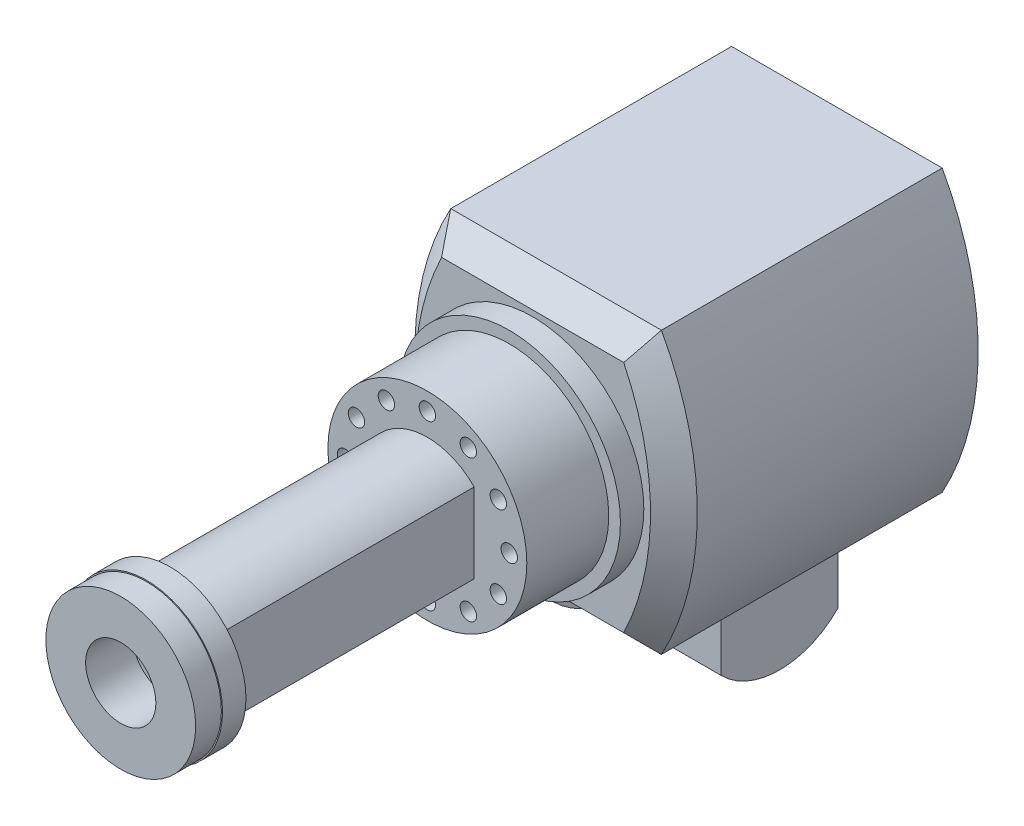
SolidWorks part; units mm, degrees
ref_plane "Front Plane" through (0, 0, 0) normal (0, 0, 1) x (1, 0, 0)
ref_plane "Top Plane" through (0, 0, 0) normal (0, 1, 0) x (1, 0, 0)
ref_plane "Right Plane" through (0, 0, 0) normal (1, 0, 0) x (0, 0, -1)
sketch "Sketch1" plane through (0, 0, 0) normal (0, 0, 1) x (1, 0, 0)
  line L0 (0, -116.0273) -> (0, 116.0273) construction
  line L1 (57.0057, 0) -> (-57.0057, 0) construction
  line L2 (45, 60) -> (-45, 60)
  line L3 (45, -60) -> (-45, -60)
  arc A0 (-45, 60) -> (-45, -60) centre (64.6586, 0) ccw
  arc A1 (45, 60) -> (45, -60) centre (-64.6586, 0) cw
  point P4 (0, 0)
  point P8 (0, 0)
  point P11 (0, 60)
  dimension "D3" = 125
  dimension "D1" = 60
  dimension "D2" = 90
extrude "Boss-Extrude1" add sketch "Sketch1" along normal blind 120 contours A1 L3 A0 L2
sketch "Sketch2" plane through (0, 0, 120) normal (0, 0, 1) x (1, 0, 0)
  line L2 (45, 60) -> (-45, 60)
  line L3 (-45, -60) -> (45, -60)
  line L4 (45, 60) -> (-45, 60)
  line L5 (-45, -60) -> (45, -60)
  arc A2 (-45, 60) -> (-45, -60) centre (64.6586, 0) ccw
  arc A3 (45, -60) -> (45, 60) centre (-64.6586, 0) ccw
  arc A4 (-45, 60) -> (-45, -60) centre (64.6586, 0) ccw
  arc A5 (45, -60) -> (45, 60) centre (-64.6586, 0) ccw
  dimension "D1" = 0
extrude "Boss-Extrude2" add sketch "Sketch2" along normal blind 10 draft 45
sketch "Sketch3" plane through (0, 0, 130) normal (0, 0, 1) x (1, 0, 0)
  circle A0 centre (0, 0) radius 47.5
  dimension "D1" = 95
extrude "Boss-Extrude3" add sketch "Sketch3" along normal blind 10
sketch "Sketch4" plane through (0, 0, 140) normal (0, 0, 1) x (1, 0, 0)
  circle A0 centre (0, 0) radius 42.5
  dimension "D1" = 85
extrude "Boss-Extrude4" add sketch "Sketch4" along normal blind 35
sketch "Sketch5" plane through (0, 0, 175) normal (0, 0, 1) x (1, 0, 0)
  line L0 (0, 0) -> (35, 0) construction
  line L1 (0, 0) -> (0, 18.3929) construction
  line L2 (0, 0) -> (13.349, 13.349) construction
  line L3 (0, 0) -> (6.8612, 11.8839) construction
  line L4 (0, 0) -> (30.3109, 17.5) construction
  circle A0 centre (35, 0) radius 3.5
  circle A14 centre (0, 35) radius 3.5
  circle A15 centre (30.3109, 17.5) radius 3.5
  circle A16 centre (17.5, 30.3109) radius 3.5
  circle A17 centre (30.3109, -17.5) radius 3.5
  circle A18 centre (17.5, -30.3109) radius 3.5
  circle A19 centre (0, -35) radius 3.5
  circle A20 centre (-17.5, -30.3109) radius 3.5
  circle A21 centre (-30.3109, -17.5) radius 3.5
  circle A22 centre (-35, 0) radius 3.5
  circle A23 centre (-30.3109, 17.5) radius 3.5
  circle A24 centre (-17.5, 30.3109) radius 3.5
  dimension "D2" = 7
  dimension "D1" = 35
extrude "Cut-Extrude1" cut sketch "Sketch5" against normal blind 10 contours A22 | A23 | A24 | A14 | A16 | A15 | A0 | A17 | A18 | A20 | A19 | A21
sketch "Sketch6" plane through (0, 0, 175) normal (0, 0, 1) x (1, 0, 0)
  line L0 (24.0929, 0) -> (-24.0929, 0) construction
  line L1 (0, -22.8589) -> (0, 22.8589) construction
  line L2 (-20, -17) -> (-20, 17)
  line L3 (20, -17) -> (20, 17)
  arc A0 (-20, 17) -> (20, 17) centre (0, -2.5959) cw
  arc A1 (-20, -17) -> (20, -17) centre (0, 2.5959) ccw
  point P5 (0, 0)
  point P9 (0, 0)
  point P12 (-20, 0)
  dimension "D3" = 28
  dimension "D1" = 34
  dimension "D2" = 20
extrude "Boss-Extrude5" add sketch "Sketch6" along normal blind 110
sketch "Sketch7" plane through (0, 0, 285) normal (0, 0, 1) x (1, 0, 0)
  circle A0 centre (0, 0) radius 32.5
  dimension "D1" = 65
extrude "Boss-Extrude6" add sketch "Sketch7" along normal blind 10
sketch "Sketch8" plane through (0, 0, 295) normal (0, 0, 1) x (1, 0, 0)
  circle A0 centre (0, 0) radius 32
  dimension "D1" = 64
extrude "Boss-Extrude7" add sketch "Sketch8" along normal blind 11
ref_plane "Plane2" through (-45, 0, 0) normal (-1, 0, 0) x (0, 0, 1)
sketch "Sketch10" plane through (-45, 0, 0) normal (-1, 0, 0) x (0, 0, 1)
  line L0 (120, -60) -> (0, -60) construction
  circle A0 centre (60, -60) radius 45
  dimension "D1" = 90
extrude "Boss-Extrude9" add sketch "Sketch10" along normal mid plane 31
sketch "Sketch11" plane through (-29.5, 0, 0) normal (1, 0, 0) x (0, 0, -1)
  line L0 (-60, -60) -> (-60, -117.8446) construction
  line L1 (-120, -60) -> (0, -60) construction
  line L2 (-85, -60) -> (-35, -60)
  line L3 (-105, -60) -> (-15, -60) construction
  line L4 (-35, -60) -> (-35, -90)
  line L5 (-85, -60) -> (-85, -90)
  arc A0 (-35, -90) -> (-85, -90) centre (-60, -65.5051) cw
  point P9 (-60, -60)
  dimension "D3" = 35
  dimension "D1" = 30
  dimension "D2" = 25
extrude "Boss-Extrude10" add sketch "Sketch11" along normal blind 65
sketch "Sketch12" plane through (0, 0, 306) normal (0, 0, 1) x (1, 0, 0)
  circle A0 centre (0, 0) radius 15
  dimension "D1" = 30
extrude "Cut-Extrude2" cut sketch "Sketch12" against normal blind 20
sketch "Sketch13" plane through (-60.5, 0, 0) normal (-1, 0, 0) x (0, 0, 1)
  circle A0 centre (60, -60) radius 17.5
  dimension "D1" = 35
extrude "Cut-Extrude3" cut sketch "Sketch13" against normal blind 22
